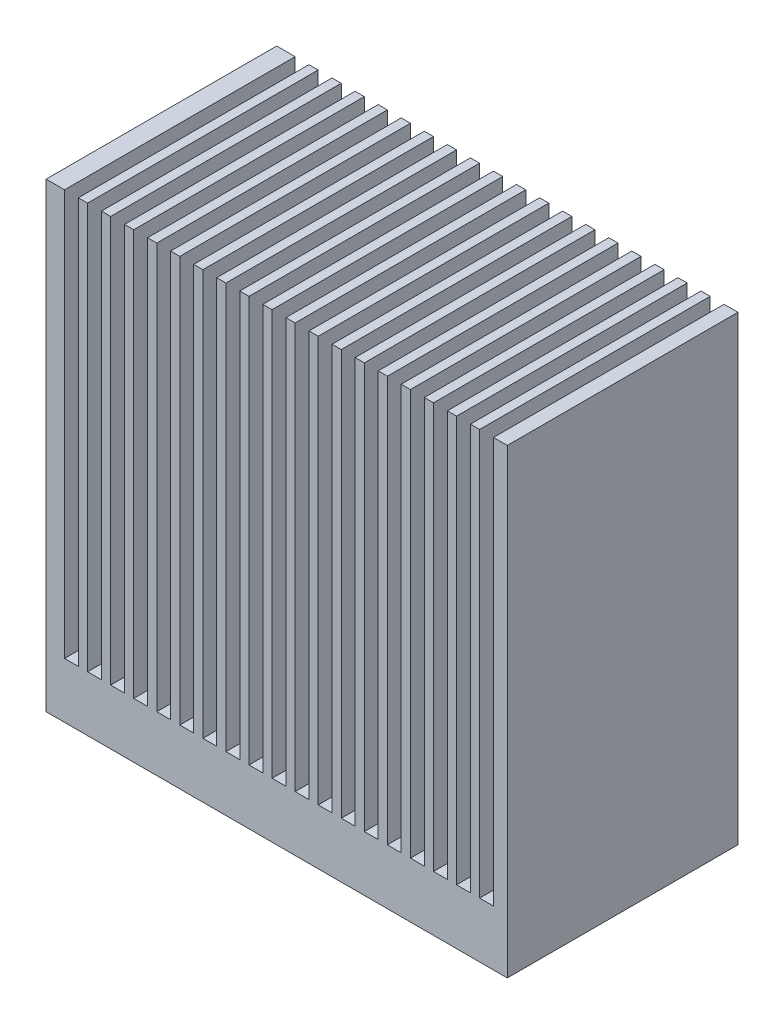
SolidWorks part; units mm, degrees
ref_plane "前视基准面" through (0, 0, 0) normal (0, 0, 1) x (1, 0, 0)
ref_plane "上视基准面" through (0, 0, 0) normal (0, 1, 0) x (1, 0, 0)
ref_plane "右视基准面" through (0, 0, 0) normal (1, 0, 0) x (0, 0, -1)
sketch "草图1" plane through (0, 0, 0) normal (0, 1, 0) x (1, 0, 0)
  line L0 (-38.2837, 0) -> (40.4297, 0) construction
  line L1 (-25, 12.5) -> (25, 12.5)
  line L2 (-25, 12.5) -> (-25, -12.5)
  line L3 (-25, -12.5) -> (25, -12.5)
  line L4 (25, 12.5) -> (25, -12.5)
  line L5 (0, 27.2258) -> (0, -28.9127) construction
  dimension "D1" = 50
  dimension "D2" = 25
extrude "拉伸1" add sketch "草图1" along normal blind 50
sketch "草图2" plane through (0, 50, 0) normal (0, 1, 0) x (-1, 0, 0)
  line L0 (1, -20.8895) -> (1, 19.2743) construction
  line L1 (-25, -12.5) -> (25, -12.5) construction
  line L2 (-1, -12.5) -> (0.5, -12.5)
  line L3 (-1, -12.5) -> (-1, 12.5)
  line L4 (-1, 12.5) -> (0.5, 12.5)
  line L5 (0.5, -12.5) -> (0.5, 12.5)
  line L6 (25, 12.5) -> (-25, 12.5) construction
  line L7 (1.5, -12.5) -> (3, -12.5)
  line L8 (1.5, -12.5) -> (1.5, 12.5)
  line L9 (1.5, 12.5) -> (3, 12.5)
  line L10 (3, -12.5) -> (3, 12.5)
  line L11 (4, -12.5) -> (5.5, -12.5)
  line L12 (4, -12.5) -> (4, 12.5)
  line L13 (4, 12.5) -> (5.5, 12.5)
  line L14 (5.5, -12.5) -> (5.5, 12.5)
  line L15 (6.5, -12.5) -> (8, -12.5)
  line L16 (6.5, -12.5) -> (6.5, 12.5)
  line L17 (6.5, 12.5) -> (8, 12.5)
  line L18 (8, -12.5) -> (8, 12.5)
  line L19 (9, -12.5) -> (10.5, -12.5)
  line L20 (9, -12.5) -> (9, 12.5)
  line L21 (9, 12.5) -> (10.5, 12.5)
  line L22 (10.5, -12.5) -> (10.5, 12.5)
  line L23 (11.5, -12.5) -> (13, -12.5)
  line L24 (11.5, -12.5) -> (11.5, 12.5)
  line L25 (11.5, 12.5) -> (13, 12.5)
  line L26 (13, -12.5) -> (13, 12.5)
  line L27 (14, -12.5) -> (15.5, -12.5)
  line L28 (14, -12.5) -> (14, 12.5)
  line L29 (14, 12.5) -> (15.5, 12.5)
  line L30 (15.5, -12.5) -> (15.5, 12.5)
  line L31 (16.5, -12.5) -> (18, -12.5)
  line L32 (16.5, -12.5) -> (16.5, 12.5)
  line L33 (16.5, 12.5) -> (18, 12.5)
  line L34 (18, -12.5) -> (18, 12.5)
  line L35 (19, -12.5) -> (20.5, -12.5)
  line L36 (19, -12.5) -> (19, 12.5)
  line L37 (19, 12.5) -> (20.5, 12.5)
  line L38 (20.5, -12.5) -> (20.5, 12.5)
  line L39 (21.5, -12.5) -> (23, -12.5)
  line L40 (21.5, -12.5) -> (21.5, 12.5)
  line L41 (21.5, 12.5) -> (23, 12.5)
  line L42 (23, -12.5) -> (23, 12.5)
  line L63 (-3.5, -12.5) -> (-2, -12.5)
  line L64 (-3.5, -12.5) -> (-3.5, 12.5)
  line L65 (-3.5, 12.5) -> (-2, 12.5)
  line L66 (-2, -12.5) -> (-2, 12.5)
  line L67 (-6, -12.5) -> (-4.5, -12.5)
  line L68 (-6, -12.5) -> (-6, 12.5)
  line L69 (-6, 12.5) -> (-4.5, 12.5)
  line L70 (-4.5, -12.5) -> (-4.5, 12.5)
  line L71 (-8.5, -12.5) -> (-7, -12.5)
  line L72 (-8.5, -12.5) -> (-8.5, 12.5)
  line L73 (-8.5, 12.5) -> (-7, 12.5)
  line L74 (-7, -12.5) -> (-7, 12.5)
  line L75 (-11, -12.5) -> (-9.5, -12.5)
  line L76 (-11, -12.5) -> (-11, 12.5)
  line L77 (-11, 12.5) -> (-9.5, 12.5)
  line L78 (-9.5, -12.5) -> (-9.5, 12.5)
  line L79 (-13.5, -12.5) -> (-12, -12.5)
  line L80 (-13.5, -12.5) -> (-13.5, 12.5)
  line L81 (-13.5, 12.5) -> (-12, 12.5)
  line L82 (-12, -12.5) -> (-12, 12.5)
  line L83 (-16, -12.5) -> (-14.5, -12.5)
  line L84 (-16, -12.5) -> (-16, 12.5)
  line L85 (-16, 12.5) -> (-14.5, 12.5)
  line L86 (-14.5, -12.5) -> (-14.5, 12.5)
  line L87 (-18.5, -12.5) -> (-17, -12.5)
  line L88 (-18.5, -12.5) -> (-18.5, 12.5)
  line L89 (-18.5, 12.5) -> (-17, 12.5)
  line L90 (-17, -12.5) -> (-17, 12.5)
  line L91 (-21, -12.5) -> (-19.5, -12.5)
  line L92 (-21, -12.5) -> (-21, 12.5)
  line L93 (-21, 12.5) -> (-19.5, 12.5)
  line L94 (-19.5, -12.5) -> (-19.5, 12.5)
  line L95 (-23.5, -12.5) -> (-22, -12.5)
  line L96 (-23.5, -12.5) -> (-23.5, 12.5)
  line L97 (-23.5, 12.5) -> (-22, 12.5)
  line L98 (-22, -12.5) -> (-22, 12.5)
  line L115 (-26, -12.5) -> (-24.5, -12.5) [skipped]
  line L116 (-26, -12.5) -> (-26, 12.5) [skipped]
  line L117 (-26, 12.5) -> (-24.5, 12.5) [skipped]
  line L118 (-24.5, -12.5) -> (-24.5, 12.5) [skipped]
  line L119 (-28.5, -12.5) -> (-27, -12.5) [skipped]
  line L120 (-28.5, -12.5) -> (-28.5, 12.5) [skipped]
  line L121 (-28.5, 12.5) -> (-27, 12.5) [skipped]
  line L122 (-27, -12.5) -> (-27, 12.5) [skipped]
  line L123 (-31, -12.5) -> (-29.5, -12.5) [skipped]
  line L124 (-31, -12.5) -> (-31, 12.5) [skipped]
  line L125 (-31, 12.5) -> (-29.5, 12.5) [skipped]
  line L126 (-29.5, -12.5) -> (-29.5, 12.5) [skipped]
  line L127 (-33.5, -12.5) -> (-32, -12.5) [skipped]
  line L128 (-33.5, -12.5) -> (-33.5, 12.5) [skipped]
  line L129 (-33.5, 12.5) -> (-32, 12.5) [skipped]
  line L130 (-32, -12.5) -> (-32, 12.5) [skipped]
  line L131 (24, -12.5) -> (25.5, -12.5) [skipped]
  line L132 (24, -12.5) -> (24, 12.5) [skipped]
  line L133 (24, 12.5) -> (25.5, 12.5) [skipped]
  line L134 (25.5, -12.5) -> (25.5, 12.5) [skipped]
  line L135 (26.5, -12.5) -> (28, -12.5) [skipped]
  line L136 (26.5, -12.5) -> (26.5, 12.5) [skipped]
  line L137 (26.5, 12.5) -> (28, 12.5) [skipped]
  line L138 (28, -12.5) -> (28, 12.5) [skipped]
  line L139 (29, -12.5) -> (30.5, -12.5) [skipped]
  line L140 (29, -12.5) -> (29, 12.5) [skipped]
  line L141 (29, 12.5) -> (30.5, 12.5) [skipped]
  line L142 (30.5, -12.5) -> (30.5, 12.5) [skipped]
  line L143 (31.5, -12.5) -> (33, -12.5) [skipped]
  line L144 (31.5, -12.5) -> (31.5, 12.5) [skipped]
  line L145 (31.5, 12.5) -> (33, 12.5) [skipped]
  line L146 (33, -12.5) -> (33, 12.5) [skipped]
  line L147 (34, -12.5) -> (35.5, -12.5) [skipped]
  line L148 (34, -12.5) -> (34, 12.5) [skipped]
  line L149 (34, 12.5) -> (35.5, 12.5) [skipped]
  line L150 (35.5, -12.5) -> (35.5, 12.5) [skipped]
  dimension "D1" = 1.5
  dimension "D2" = 0.5
  dimension "D3" = 1
extrude "切除-拉伸1" cut sketch "草图2" against normal offset from surface (44 mm away) 6 up to face at (0, 0, 0)
